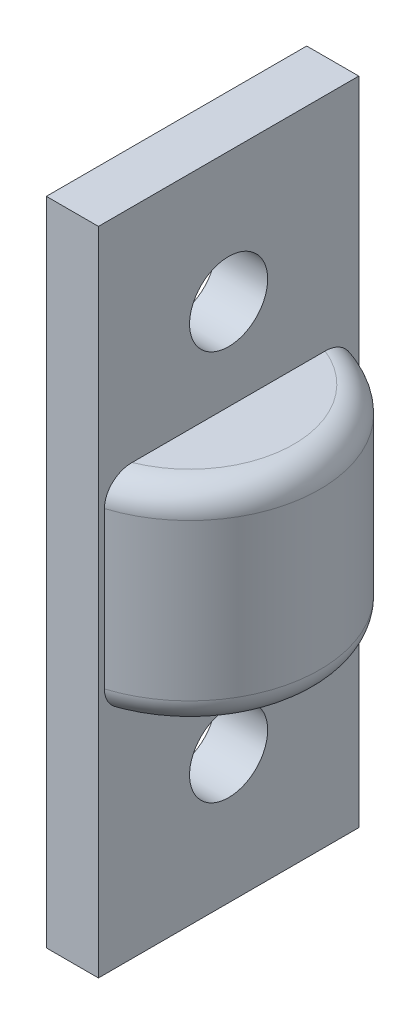
SolidWorks part; units mm, degrees
ref_plane "Front" through (0, 0, 0) normal (0, 0, 1) x (1, 0, 0)
ref_plane "Top" through (0, 0, 0) normal (0, 1, 0) x (1, 0, 0)
ref_plane "Right" through (0, 0, 0) normal (1, 0, 0) x (0, 0, -1)
sketch "Sketch1" plane through (-20.145, 0, 0) normal (1, 0, 0) x (0, 0, -1)
  line L0 (5, 36) -> (-5, 36) construction
  line L1 (5, 44) -> (-5, 44) construction
  line L2 (5, 36) -> (-5, 36)
  line L3 (5, 44) -> (-5, 44)
  line L4 (5, 52.5) -> (5, 27.5)
  line L5 (5, 75) -> (5, 27.967) construction
  line L6 (5, 27.5) -> (-5, 27.5)
  line L7 (-5, 26.6505) -> (-5, 75) construction
  line L8 (-5, 27.5) -> (-5, 52.5)
  line L9 (-5, 52.5) -> (5, 52.5)
  line L10 (0, 52.5) -> (0, 27.5) construction
  circle A23 centre (0, 47.5) radius 1.5
  circle A24 centre (0, 32.5) radius 1.5
  point P0 (0, 32.5)
  point P2 (0, 47.5)
  point P19 (0, 40)
  dimension "D2" = 3
  dimension "D3" = 3
  dimension "D1" = 25
extrude "Boss-Extrude1" add sketch "Sketch1" along normal blind 2 contours L4 L6 L8 L9 | A23 | A24
sketch "Sketch2" plane through (0, 100, 0) normal (0, 1, 0) x (1, 0, 0)
  line L1 (-19.645, 5) -> (-19.645, -5)
  line L2 (-24.145, 5) -> (-20.145, 5) construction
  line L3 (-20.145, -4) -> (-20.145, 4) construction
  line L4 (-24.145, -5) -> (-20.145, -5) construction
  arc A0 (-19.645, 5) -> (-19.645, -5) centre (-19.645, 0) cw
  dimension "D1" = 0.5
extrude "Boss-Extrude2" add sketch "Sketch2" against normal up to vertex (64 mm away) from vertex at -56
fillet "Fillet1" radius 1 2 edges at (-14.645, 36, 0) (-14.645, 44, 0)
